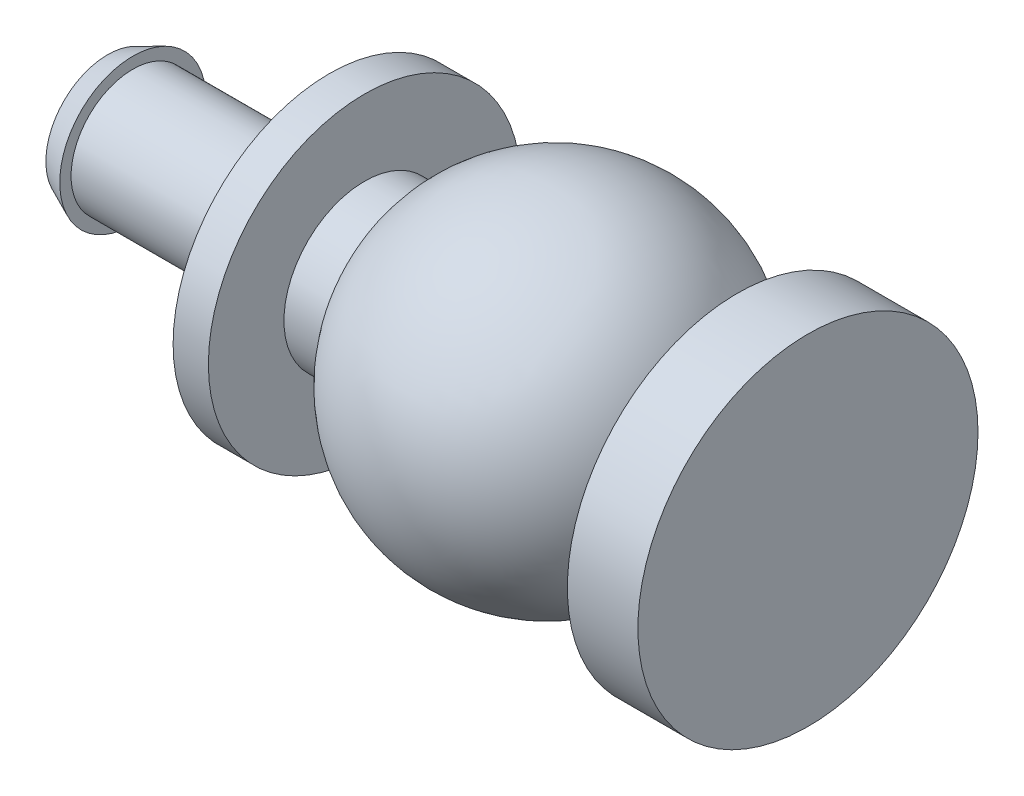
SolidWorks part; units mm, degrees
ref_plane "Ön Düzlem" through (0, 0, 0) normal (0, 0, 1) x (1, 0, 0)
ref_plane "Üst Düzlem" through (0, 0, 0) normal (0, 1, 0) x (1, 0, 0)
ref_plane "Sağ Düzlem" through (0, 0, 0) normal (1, 0, 0) x (0, 0, -1)
sketch "Çizim5" plane through (0, 0, 0) normal (0, 1, 0) x (1, 0, 0)
  line L0 (0, 0) -> (0, -2.45)
  line L1 (0, -2.45) -> (1, -2.9)
  line L2 (1, -2.9) -> (1, -2.45)
  line L3 (1, -2.45) -> (6.8, -2.45)
  line L4 (6.8, -2.45) -> (8.8, -6.2)
  line L5 (8.8, -6.2) -> (10.2, -6.2)
  line L6 (10.2, -6.2) -> (10.2, -3.2)
  line L7 (10.2, -3.2) -> (11.85, -3.2)
  line L8 (23.35, -3.2) -> (25, -3.2)
  line L9 (25, -3.2) -> (25, -6.75)
  line L10 (25, -6.75) -> (27.8, -6.75)
  line L11 (27.8, -6.75) -> (27.8, 0)
  line L12 (27.8, 0) -> (0, 0)
  line L13 (14.6011, -6.75) -> (18.3877, -6.75) construction
  arc A0 (11.85, -3.2) -> (23.35, -3.2) centre (17.6, -0.3183) ccw
  point P12 (14.6011, -7.4885)
  point P17 (13.1376, -3.2)
  point P18 (20.3391, -3.1489)
  dimension "D9" = 6.75
  dimension "D1" = 2.45
  dimension "D2" = 1
  dimension "D3" = 2.9
  dimension "D4" = 5.8
  dimension "D5" = 2
  dimension "D6" = 6.2
  dimension "D7" = 3
  dimension "D8" = 1.4
  dimension "D10" = 11.5
  dimension "D11" = 27.8
  dimension "D12" = 2.8
  dimension "D13" = 6.75
revolve "Döndür1" add sketch "Çizim5" angle 360 about L12
sketch "Çizim6" plane through (0, 0, 0) normal (-1, 0, 0) x (0, 0, 1)
  circle A0 centre (0, 0) radius 1.25
  dimension "D1" = 2.5
extrude "Kes-Ekstrüzyon1" cut sketch "Çizim6" against normal blind 4
